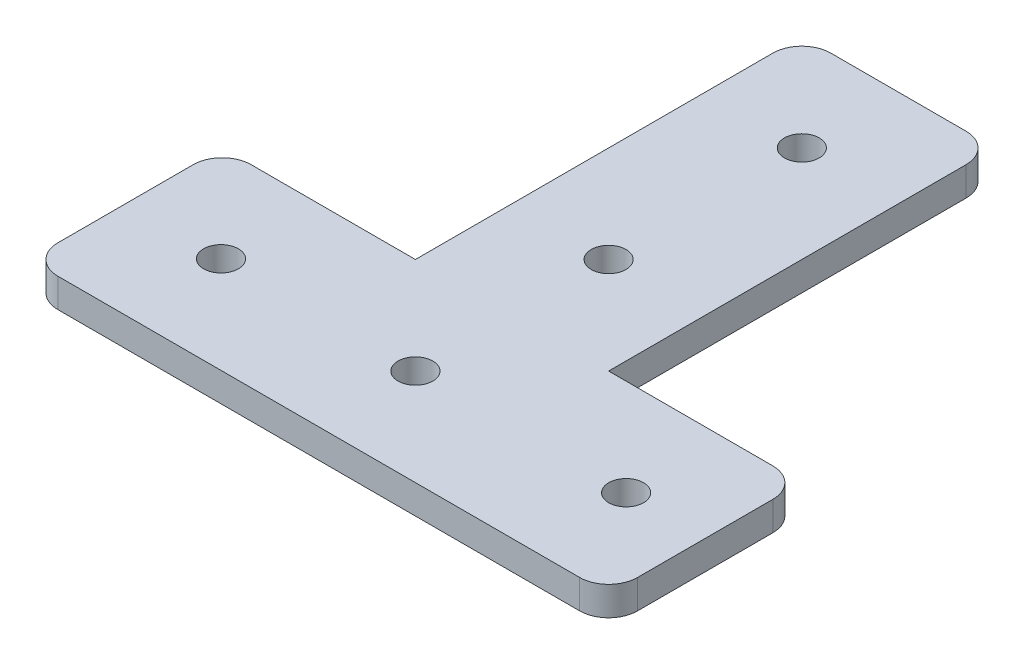
SolidWorks part; units mm, degrees
ref_plane "前视基准面" through (0, 0, 0) normal (0, 0, 1) x (1, 0, 0)
ref_plane "上视基准面" through (0, 0, 0) normal (0, 1, 0) x (1, 0, 0)
ref_plane "右视基准面" through (0, 0, 0) normal (1, 0, 0) x (0, 0, -1)
sketch "草图2" plane through (0, 0, 0) normal (0, 1, 0) x (1, 0, 0)
  line L0 (0, 0) -> (0, 18.4967) construction
  line L1 (-30, -10) -> (30, -10)
  line L2 (-30, -10) -> (-30, 10)
  line L3 (-30, 10) -> (30, 10)
  line L4 (30, -10) -> (30, 10)
  line L5 (-30, -10) -> (30, 10) construction
  line L6 (-30, 10) -> (30, -10) construction
  line L7 (-10, 50) -> (10, 50)
  line L8 (-10, 50) -> (-10, 10)
  line L9 (-10, 10) -> (10, 10)
  line L10 (10, 50) -> (10, 10)
  circle A0 centre (0, 40) radius 1.8
  circle A1 centre (0, 20) radius 1.8
  circle A2 centre (21.8128, 0) radius 1.8
  circle A3 centre (-20.1228, 0) radius 1.8
  circle A4 centre (0, 0) radius 1.8
  point P0 (0, 0)
  dimension "D5" = 3.6
  dimension "D1" = 20
  dimension "D2" = 60
  dimension "D3" = 20
  dimension "D4" = 40
  dimension "D6" = 20
  dimension "D7" = 20
extrude "凸台-拉伸1" add sketch "草图2" along normal blind 3 contours L10 L7 L8 L3 A1 A0 | L1 L4 L3 L2 A4 A3 A2
fillet "圆角1" radius 3 6 edges at (10, 1.5, -50) (30, 1.5, -10) (30, 1.5, 10) (-30, 1.5, 10) (-30, 1.5, -10) (-10, 1.5, -50)
